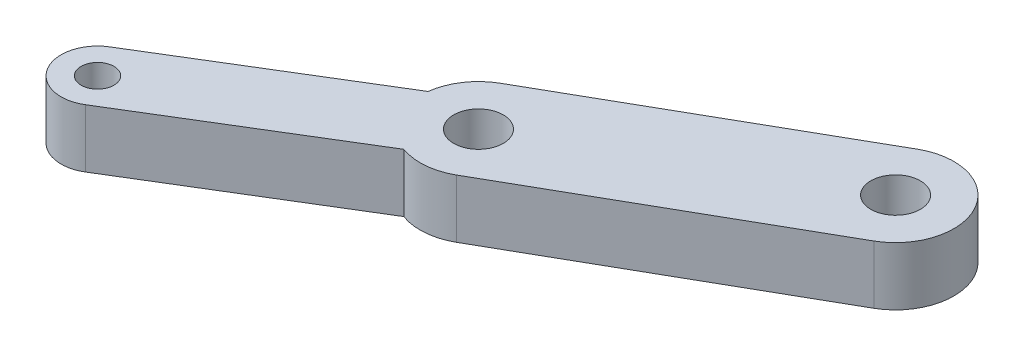
SolidWorks part; units mm, degrees
ref_plane "Front Plane" through (0, 0, 0) normal (0, 0, 1) x (1, 0, 0)
ref_plane "Top Plane" through (0, 0, 0) normal (0, 1, 0) x (1, 0, 0)
ref_plane "Right Plane" through (0, 0, 0) normal (1, 0, 0) x (0, 0, -1)
sketch "Sketch1" plane through (0, 0, 0) normal (0, 1, 0) x (1, 0, 0)
  line L0 (47.2297, 219.0186) -> (732.563, 219.0186) construction
  line L1 (-0.5598, 3.5368) -> (15.6772, 13.4344) construction
  line L2 (-1.861, 5.6715) -> (11.7098, 13.9439)
  line L4 (15.6772, 13.4344) -> (33.9033, 23.8249) construction
  line L5 (13.6962, 16.9094) -> (31.9222, 27.2999)
  line L6 (17.6583, 9.9594) -> (35.8843, 20.3499)
  line L7 (14.0637, 12.8992) -> (15.6772, 13.4344) construction
  line L8 (0.7414, 1.4022) -> (14.3123, 9.6745)
  circle A0 centre (15.6772, 13.4344) radius 1.7
  arc A1 (-1.861, 5.6715) -> (0.7414, 1.4022) centre (-0.5598, 3.5368) ccw
  circle A3 centre (33.9033, 23.8249) radius 1.7
  circle A4 centre (-0.5598, 3.5368) radius 1.125
  arc A5 (13.6962, 16.9094) -> (11.9265, 14.8243) centre (15.6772, 13.4344) ccw
  arc A6 (35.8843, 20.3499) -> (31.9222, 27.2999) centre (33.9033, 23.8249) ccw
  arc A7 (14.3123, 9.6745) -> (17.6583, 9.9594) centre (15.6772, 13.4344) ccw
  arc A8 (11.9265, 14.8243) -> (11.7098, 13.9439) centre (15.6772, 13.4344) ccw
  point P4 (7.5587, 8.4856)
  point P6 (8.5961, 10.783)
  point P14 (24.9437, 18.3779)
extrude "Boss-Extrude1" add sketch "Sketch1" along normal blind 4
